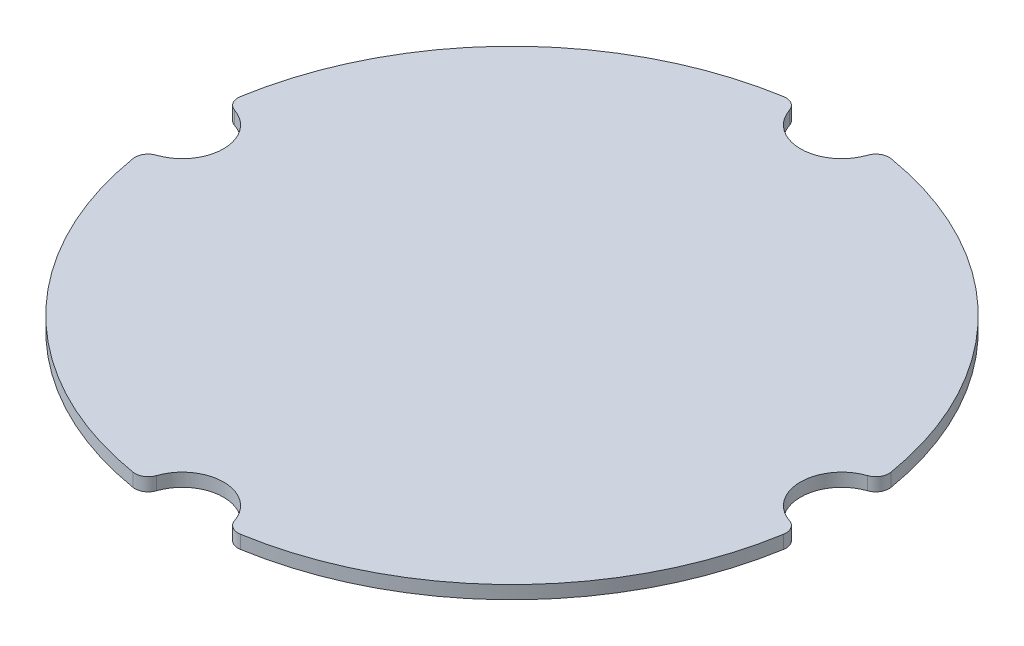
SolidWorks part; units mm, degrees
ref_plane "Front Plane" through (0, 0, 0) normal (0, 0, 1) x (1, 0, 0)
ref_plane "Top Plane" through (0, 0, 0) normal (0, 1, 0) x (1, 0, 0)
ref_plane "Right Plane" through (0, 0, 0) normal (1, 0, 0) x (0, 0, -1)
sketch "Sketch3" plane through (0, 0, 0) normal (0, 1, 0) x (1, 0, 0)
  circle A0 centre (0, 0) radius 63.5
  dimension "D1" = 127
extrude "Boss-Extrude1" add sketch "Sketch3" along normal blind 2.54
sketch "Sketch4" plane through (0, 2.54, 0) normal (0, 1, 0) x (1, 0, 0)
  circle A0 centre (0, 63.5) radius 7.9375
  circle A1 centre (0, 0) radius 63.5 construction
  point P4 (-12.2216, 62.3128)
  dimension "D1" = 15.875
extrude "Cut-Extrude1" cut sketch "Sketch4" against normal up to next
fillet "Fillet1" radius 2.54 2 edges at (7.922, 1.27, -63.0039) (-7.922, 1.27, -63.0039)
pattern_circular "CirPattern1" count 4 over 360 about axis through (0, 0, 0) along (0, 1, 0) of "Cut-Extrude1", "Fillet1"
